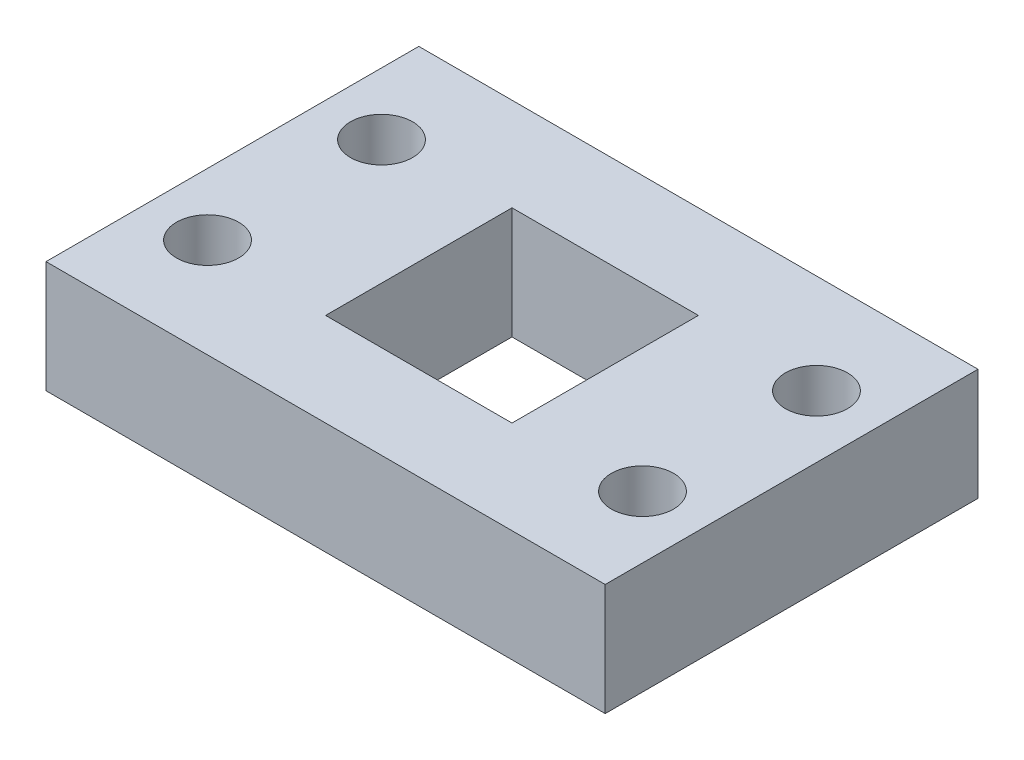
SolidWorks part; units mm, degrees
ref_plane "Alzado" through (0, 0, 0) normal (0, 0, 1) x (1, 0, 0)
ref_plane "Planta" through (0, 0, 0) normal (0, 1, 0) x (1, 0, 0)
ref_plane "Vista lateral" through (0, 0, 0) normal (1, 0, 0) x (0, 0, -1)
sketch "Croquis1" plane through (0, 0, 0) normal (0, 1, 0) x (1, 0, 0)
  line L1 (0, 0) -> (45, 0)
  line L2 (0, 0) -> (0, 30)
  line L3 (0, 30) -> (45, 30)
  line L4 (45, 0) -> (45, 30)
  dimension "D1" = 30
  dimension "D2" = 45
extrude "Saliente-Extruir1" add sketch "Croquis1" along normal blind 9
sketch "Croquis2" plane through (0, 9, 0) normal (0, 1, 0) x (1, 0, 0)
  line L0 (22.5, 0) -> (22.5, 30) construction
  line L1 (0, 0) -> (45, 0) construction
  line L2 (45, 30) -> (0, 30) construction
  line L3 (5, 15) -> (22.5, 15) construction
  line L4 (22.5, 15) -> (40, 15) construction
  line L5 (5, 8) -> (5, 15) construction
  line L6 (5, 15) -> (5, 22) construction
  line L8 (15, 7.5) -> (30, 7.5)
  line L9 (15, 7.5) -> (15, 22.5)
  line L10 (15, 22.5) -> (30, 22.5)
  line L11 (30, 7.5) -> (30, 22.5)
  line L12 (15, 7.5) -> (30, 22.5) construction
  line L13 (15, 22.5) -> (30, 7.5) construction
  circle A0 centre (5, 22) radius 2.5
  circle A1 centre (5, 8) radius 2.5
  circle A2 centre (40, 8) radius 2.5
  circle A3 centre (40, 22) radius 2.5
  dimension "D1" = 5
  dimension "D2" = 7
  dimension "D3" = 17.5
  dimension "D4" = 15
extrude "Cortar-Extruir1" cut sketch "Croquis2" against normal blind 10
